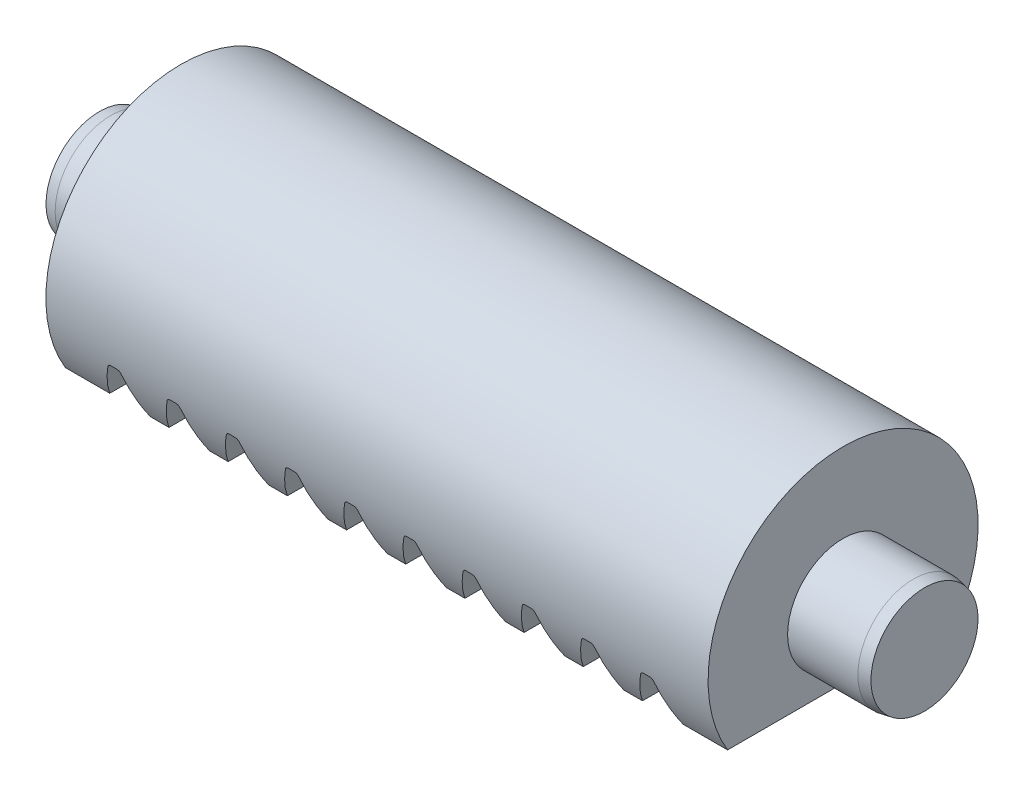
SolidWorks part; units mm, degrees
material "Простая углеродистая сталь"
ref_plane "Спереди" through (0, 0, 0) normal (0, 0, 1) x (1, 0, 0)
ref_plane "Сверху" through (0, 0, 0) normal (0, 1, 0) x (1, 0, 0)
ref_plane "Справа" through (0, 0, 0) normal (1, 0, 0) x (0, 0, -1)
sketch "Эскиз1" plane through (0, 0, 0) normal (0, 0, 1) x (1, 0, 0)
  line L0 (-162.7654, 0) -> (162.7654, 0) construction
  line L1 (-111.5, 0) -> (-111.5, 14.471)
  line L2 (-111.5, 14.471) -> (-108.5, 15)
  line L3 (-108.5, 15) -> (-89.5, 15)
  line L4 (-89.5, 15) -> (-89.5, 36.5)
  line L5 (-89.5, 36.5) -> (89.5, 36.5)
  line L6 (0, 0) -> (0, 90.612) construction
  line L7 (89.5, 15) -> (89.5, 36.5)
  line L8 (108.5, 15) -> (89.5, 15)
  line L9 (111.5, 14.471) -> (108.5, 15)
  line L10 (111.5, 0) -> (111.5, 14.471)
  line L11 (-111.5, 0) -> (111.5, 0)
  point P12 (0, 36.5)
  dimension "D1" = 10
  dimension "D2" = 3
  dimension "D3" = 30
  dimension "D4" = 73
  dimension "D5" = 22
  dimension "D6" = 223
revolve "Повернуть1" add sketch "Эскиз1" angle 360 about L0
sketch "Эскиз2" plane through (0, 0, 0) normal (0, 0, 1) x (1, 0, 0)
  line L0 (89.5, 36.5) -> (-89.5, 36.5) construction
  line L41 (89.5, -36.5) -> (89.5, 36.5) construction
  line L44 (-89.5, -18.9) -> (-89.5, -36.5)
  line L45 (-89.5, -36.5) -> (89.5, -36.5)
  line L46 (89.5, -36.5) -> (89.5, -18.9)
  line L49 (89.5, -18.9) -> (-89.5, -18.9)
  line L50 (-89.5, 36.5) -> (-89.5, -36.5) construction
  point P72 (68.6629, -10.615)
  dimension "D1" = 55.4
extrude "Вырез-Вытянуть1" cut sketch "Эскиз2" against normal through all and the other way through all
sketch "Эскиз3" plane through (0, 0, 0) normal (0, 0, 1) x (1, 0, 0)
  line L0 (77.5, -18.9) -> (73.7358, -8.558)
  line L1 (72.7961, -7.9) -> (71.2039, -7.9)
  line L2 (70.2642, -8.558) -> (66.5, -18.9)
  line L3 (66.5, -18.9) -> (77.5, -18.9)
  line L4 (89.5, -18.9) -> (89.5, 36.5) construction
  line L5 (-89.5, -18.9) -> (89.5, -18.9) construction
  arc A0 (71.2039, -7.9) -> (70.2642, -8.558) centre (71.2039, -8.9) ccw
  arc A1 (73.7358, -8.558) -> (72.7961, -7.9) centre (72.7961, -8.9) ccw
  point P10 (70.5037, -7.9)
  point P13 (73.4963, -7.9)
  dimension "D5" = 1
  dimension "D1" = 11
  dimension "D2" = 40
  dimension "D3" = 11
  dimension "D4" = 12
extrude "Вырез-Вытянуть2" cut sketch "Эскиз3" against normal through all both and the other way through all
pattern_linear "Линейный массив1" count 10 spacing 16 along (-1, 0, 0) of "Вырез-Вытянуть2"
